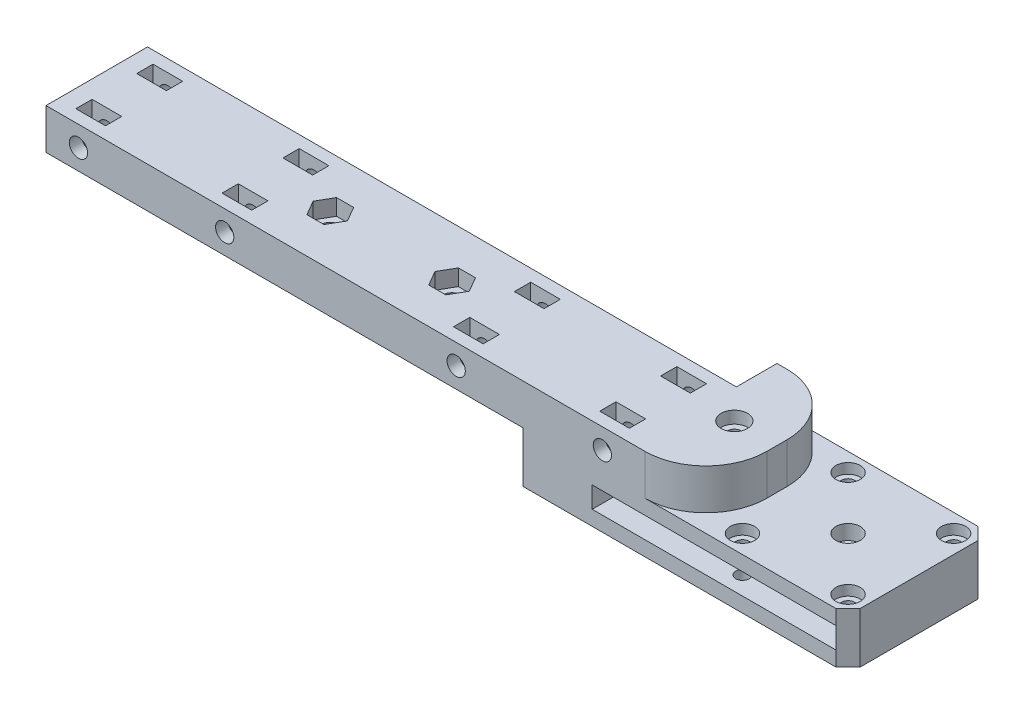
SolidWorks part; units mm, degrees
ref_plane "Front Plane" through (0, 0, 0) normal (0, 0, 1) x (1, 0, 0)
ref_plane "Top Plane" through (0, 0, 0) normal (0, 1, 0) x (1, 0, 0)
ref_plane "Right Plane" through (0, 0, 0) normal (1, 0, 0) x (0, 0, -1)
sketch "Sketch1" plane through (0, 0, 0) normal (0, 1, 0) x (1, 0, 0)
  line L7 (0, 0) -> (145, 0)
  line L8 (0, 0) -> (0, 25)
  line L9 (0, 25) -> (145, 25)
  line L10 (145, 0) -> (145, 25)
  dimension "D1" = 25
  dimension "D3" = 145
extrude "Boss-Extrude1" add sketch "Sketch1" along normal blind 10
sketch "Sketch2" plane through (0, 10, 0) normal (0, 1, 0) x (1, 0, 0)
  line L5 (145, 0) -> (162.5, 0)
  line L6 (145, 0) -> (145, 35)
  line L7 (145, 35) -> (162.5, 35)
  line L8 (162.5, 0) -> (162.5, 35)
  dimension "D1" = 17.5
  dimension "D2" = 35
extrude "Boss-Extrude2" add sketch "Sketch2" against normal blind 10
sketch "Sketch4" plane through (0, 0, 0) normal (0, -1, 0) x (1, 0, 0)
  line L0 (162.5, -35) -> (197.5, -35) construction
  line L1 (162.5, 0) -> (117.5, 0) construction
  line L2 (0, 0) -> (162.5, 0) construction
  line L4 (117.5, 0) -> (197.5, 0)
  line L5 (117.5, 0) -> (117.5, -35)
  line L6 (117.5, -35) -> (197.5, -35)
  line L7 (197.5, 0) -> (197.5, -35)
  dimension "D1" = 35
  dimension "D2" = 45
extrude "Boss-Extrude3" add sketch "Sketch4" along normal blind 12.5
sketch "Sketch8" plane through (0, 0, -25) normal (0, 0, -1) x (-1, 0, 0)
  line L0 (-145, 5) -> (0, 5) construction
  line L1 (-145, 10) -> (-145, 0) construction
  line L2 (0, 10) -> (0, 0) construction
  line L3 (-72.5, 10) -> (-72.5, 0) construction
  line L4 (0, 10) -> (-145, 10) construction
  line L5 (0, 0) -> (-117.5, 0) construction
  circle A0 centre (-137, 5) radius 2.25
  circle A1 centre (-101, 5) radius 2.25
  circle A2 centre (-44, 5) radius 2.25
  circle A3 centre (-8, 5) radius 2.25
  dimension "D1" = 8
  dimension "D2" = 4.5
  dimension "D4" = 36
  dimension "D3" = 2
extrude "Cut-Extrude5" cut sketch "Sketch8" against normal through all
sketch "Sketch9" plane through (0, 10, 0) normal (0, 1, 0) x (1, 0, 0)
  line L0 (145, 25) -> (145, 0) construction
  line L1 (0, 0) -> (162.5, 0) construction
  line L2 (145, 12.5) -> (0, 12.5) construction
  line L3 (0, 0) -> (0, 25) construction
  line L4 (72.5, 25) -> (72.5, 0) construction
  line L5 (0, 25) -> (145, 25) construction
  line L6 (137, 0) -> (137, 25) construction
  line L7 (140.65, 22) -> (133.35, 22)
  line L8 (140.65, 7) -> (133.35, 7)
  line L9 (140.65, 7) -> (140.65, 3)
  line L10 (140.65, 3) -> (133.35, 3)
  line L11 (133.35, 7) -> (133.35, 3)
  line L12 (140.65, 7) -> (133.35, 3) construction
  line L13 (140.65, 3) -> (133.35, 7) construction
  line L14 (133.35, 18) -> (133.35, 22)
  line L15 (140.65, 18) -> (133.35, 18)
  line L16 (140.65, 18) -> (140.65, 22)
  line L17 (104.65, 7) -> (104.65, 3)
  line L18 (104.65, 7) -> (97.35, 7)
  line L19 (97.35, 7) -> (97.35, 3)
  line L20 (104.65, 3) -> (97.35, 3)
  line L21 (104.65, 22) -> (97.35, 22)
  line L22 (97.35, 18) -> (97.35, 22)
  line L23 (104.65, 18) -> (97.35, 18)
  line L24 (104.65, 18) -> (104.65, 22)
  line L25 (4.35, 18) -> (4.35, 22)
  line L26 (4.35, 18) -> (11.65, 18)
  line L27 (11.65, 18) -> (11.65, 22)
  line L28 (4.35, 22) -> (11.65, 22)
  line L29 (40.35, 18) -> (40.35, 22)
  line L30 (40.35, 18) -> (47.65, 18)
  line L31 (47.65, 18) -> (47.65, 22)
  line L32 (40.35, 22) -> (47.65, 22)
  line L33 (40.35, 7) -> (47.65, 7)
  line L34 (47.65, 7) -> (47.65, 3)
  line L35 (40.35, 3) -> (47.65, 3)
  line L36 (40.35, 7) -> (40.35, 3)
  line L37 (4.35, 3) -> (11.65, 3)
  line L38 (11.65, 7) -> (11.65, 3)
  line L39 (4.35, 7) -> (11.65, 7)
  line L40 (4.35, 7) -> (4.35, 3)
  point P15 (137, 5)
  dimension "D1" = 8
  dimension "D2" = 5
  dimension "D3" = 7.3
  dimension "D4" = 4
  dimension "D6" = 36
  dimension "D5" = 2
extrude "Cut-Extrude6" cut sketch "Sketch9" against normal up to surface (10 mm away) up to face at (58.75, 0, -12.5)
sketch "Sketch10" plane through (0, 0, 0) normal (0, 1, 0) x (1, 0, 0)
  line L0 (197.5, 17.5) -> (162.5, 17.5) construction
  line L1 (197.5, 35) -> (197.5, 0) construction
  line L2 (162.5, 0) -> (162.5, 35) construction
  line L3 (180, 0) -> (180, 35) construction
  line L6 (197.5, 0) -> (162.5, 0) construction
  line L7 (162.5, 35) -> (197.5, 35) construction
  circle A1 centre (180, 17.5) radius 3
  circle A2 centre (193, 4.5) radius 1.65
  circle A3 centre (167, 4.5) radius 1.65
  circle A4 centre (167, 30.5) radius 1.65
  circle A5 centre (193, 30.5) radius 1.65
  dimension "D1" = 6
  dimension "D2" = 3.3
  dimension "D3" = 13
  dimension "D4" = 13
  dimension "D5" = 17.5
extrude "Cut-Extrude7" cut sketch "Sketch10" against normal up to next
chamfer "Chamfer1" distance 3 angle 45 2 edges at (197.5, -6.25, -35) (197.5, -6.25, 0)
fillet "Fillet1" radius 15 2 edges at (162.5, 5, 0) (162.5, 5, -35)
sketch "Sketch14" plane through (0, -12.5, 0) normal (0, -1, 0) x (1, 0, 0)
  circle A0 centre (180, -17.5) radius 11.25
  dimension "D1" = 22.5
extrude "Cut-Extrude11" cut sketch "Sketch14" against normal blind 2.5
sketch "Sketch15" plane through (0, 0, 0) normal (0, 1, 0) x (1, 0, 0)
  line L0 (167, 30.5) -> (193, 30.5) construction
  line L1 (167, 4.5) -> (193, 4.5) construction
  line L2 (180, 30.5) -> (180, 4.5) construction
  line L3 (197.5, 17.5) -> (180, 17.5) construction
  line L4 (197.5, 32) -> (197.5, 3) construction
  circle A0 centre (167, 30.5) radius 3
  circle A1 centre (193, 30.5) radius 3
  circle A2 centre (193, 4.5) radius 3
  circle A3 centre (167, 4.5) radius 3
  dimension "D1" = 6
extrude "Cut-Extrude12" cut sketch "Sketch15" against normal blind 2.5
sketch "Sketch16" plane through (0, 10, 0) normal (0, 1, 0) x (1, 0, 0)
  line L0 (52, 25) -> (52, 0) construction
  line L1 (0, 25) -> (145, 25) construction
  line L2 (0, 0) -> (147.5, 0) construction
  line L3 (0, 0) -> (0, 25) construction
  line L4 (93, 25) -> (93, 0) construction
  line L5 (52, 12.5) -> (93, 12.5) construction
  line L6 (72.5, 12.5) -> (72.5, 0) construction
  circle A0 centre (57.5, 12.5) radius 2.25
  circle A1 centre (87.5, 12.5) radius 2.25
  dimension "D3" = 4.5
  dimension "D4" = 15
  dimension "D5" = 30
  dimension "D6" = 57.5
  dimension "D1" = 52
  dimension "D2" = 93
extrude "Cut-Extrude13" cut sketch "Sketch16" against normal up to next
sketch "Sketch18" plane through (0, 10, 0) normal (0, 1, 0) x (1, 0, 0)
  line L0 (87.5, 12.5) -> (57.5, 12.5) construction
  line L1 (72.5, 12.5) -> (72.5, 0) construction
  line L2 (83.2853, 12.5) -> (85.3927, 8.85)
  line L3 (85.3927, 8.85) -> (89.6073, 8.85)
  line L4 (89.6073, 8.85) -> (91.7147, 12.5)
  line L5 (91.7147, 12.5) -> (89.6073, 16.15)
  line L6 (89.6073, 16.15) -> (85.3927, 16.15)
  line L7 (85.3927, 16.15) -> (83.2853, 12.5)
  line L8 (0, 0) -> (147.5, 0) construction
  line L9 (59.6073, 16.15) -> (61.7147, 12.5)
  line L10 (55.3927, 16.15) -> (59.6073, 16.15)
  line L11 (53.2853, 12.5) -> (55.3927, 16.15)
  line L12 (55.3927, 8.85) -> (53.2853, 12.5)
  line L13 (59.6073, 8.85) -> (55.3927, 8.85)
  line L14 (61.7147, 12.5) -> (59.6073, 8.85)
  circle A0 centre (87.5, 12.5) radius 3.65 construction
  dimension "D1" = 7.3
  dimension "D2" = 3.65
extrude "Cut-Extrude15" cut sketch "Sketch18" against normal blind 4
sketch "Sketch19" plane through (0, 0, 0) normal (0, 0, 1) x (1, 0, 0)
  line L0 (194.5, -6.25) -> (117.5, -6.25) construction
  line L1 (194.5, -12.5) -> (194.5, 0) construction
  line L2 (117.5, -12.5) -> (117.5, 0) construction
  line L3 (197.5, -12.5) -> (197.5, 0) construction
  line L4 (134.5, -8.85) -> (194.5, -8.85)
  line L5 (134.5, -8.85) -> (134.5, -3.65)
  line L6 (134.5, -3.65) -> (194.5, -3.65)
  line L7 (194.5, -8.85) -> (194.5, -3.65)
  line L8 (134.5, -8.85) -> (194.5, -3.65) construction
  line L9 (134.5, -3.65) -> (194.5, -8.85) construction
  line L10 (117.5, -12.5) -> (117.5, 0) construction
  line L11 (117.5, -12.5) -> (194.5, -12.5) construction
  point P6 (164.5, -6.25)
  dimension "D1" = 60
  dimension "D2" = 5.2
  dimension "D3" = 3
  dimension "D4" = 47
  dimension "D5" = 3.65
extrude "Cut-Extrude16" cut sketch "Sketch19" against normal up to next
sketch "Sketch20" plane through (0, 10, 0) normal (0, 1, 0) x (1, 0, 0)
  line L0 (180, 17.5) -> (152, 17.5) construction
  line L1 (147.5, 35) -> (194.5, 35) construction
  circle A0 centre (152, 17.5) radius 1.75
  dimension "D2" = 3.5
  dimension "D4" = 17.5
  dimension "D1" = 28
  dimension "D3" = 152
extrude "Cut-Extrude17" cut sketch "Sketch20" against normal through all
sketch "Sketch21" plane through (0, -12.5, 0) normal (0, -1, 0) x (1, 0, 0)
  line L1 (140, -29.5) -> (164, -29.5)
  line L2 (140, -29.5) -> (140, -5.5)
  line L3 (140, -5.5) -> (164, -5.5)
  line L4 (164, -29.5) -> (164, -5.5)
  line L5 (140, -29.5) -> (164, -5.5) construction
  line L6 (140, -5.5) -> (164, -29.5) construction
  point P0 (152, -17.5)
  dimension "D1" = 24
  dimension "D2" = 24
extrude "Cut-Extrude18" cut sketch "Sketch21" against normal blind 2
sketch "Sketch22" plane through (0, -10.5, 0) normal (0, -1, 0) x (1, 0, 0)
  line L0 (152, -5.5) -> (152, -29.5) construction
  line L1 (164, -5.5) -> (140, -5.5) construction
  line L2 (140, -29.5) -> (164, -29.5) construction
  line L3 (140, -17.5) -> (164, -17.5) construction
  line L4 (140, -5.5) -> (140, -29.5) construction
  line L5 (164, -29.5) -> (164, -5.5) construction
  line L7 (144, -22) -> (160, -22)
  line L8 (144, -22) -> (144, -13)
  line L9 (144, -13) -> (160, -13)
  line L10 (160, -22) -> (160, -13)
  line L11 (144, -22) -> (160, -13) construction
  line L12 (144, -13) -> (160, -22) construction
  circle A0 centre (144, -9.5) radius 1.65
  circle A1 centre (160, -9.5) radius 1.65
  circle A2 centre (160, -25.5) radius 1.65
  circle A3 centre (144, -25.5) radius 1.65
  point P20 (152, -17.5)
  dimension "D1" = 8
  dimension "D2" = 8
  dimension "D3" = 3.3
  dimension "D4" = 9
  dimension "D5" = 16
extrude "Cut-Extrude19" cut sketch "Sketch22" against normal up to next
sketch "Sketch23" plane through (0, 10, 0) normal (0, 1, 0) x (1, 0, 0)
  circle A0 centre (152, 17.5) radius 3.25
  dimension "D1" = 6.5
extrude "Cut-Extrude20" cut sketch "Sketch23" against normal blind 3
sketch "Sketch24" plane through (0, -3.65, 0) normal (0, -1, 0) x (1, 0, 0)
  circle A0 centre (152, -17.5) radius 3.25
  dimension "D1" = 6.5
extrude "Cut-Extrude21" cut sketch "Sketch24" against normal blind 3
